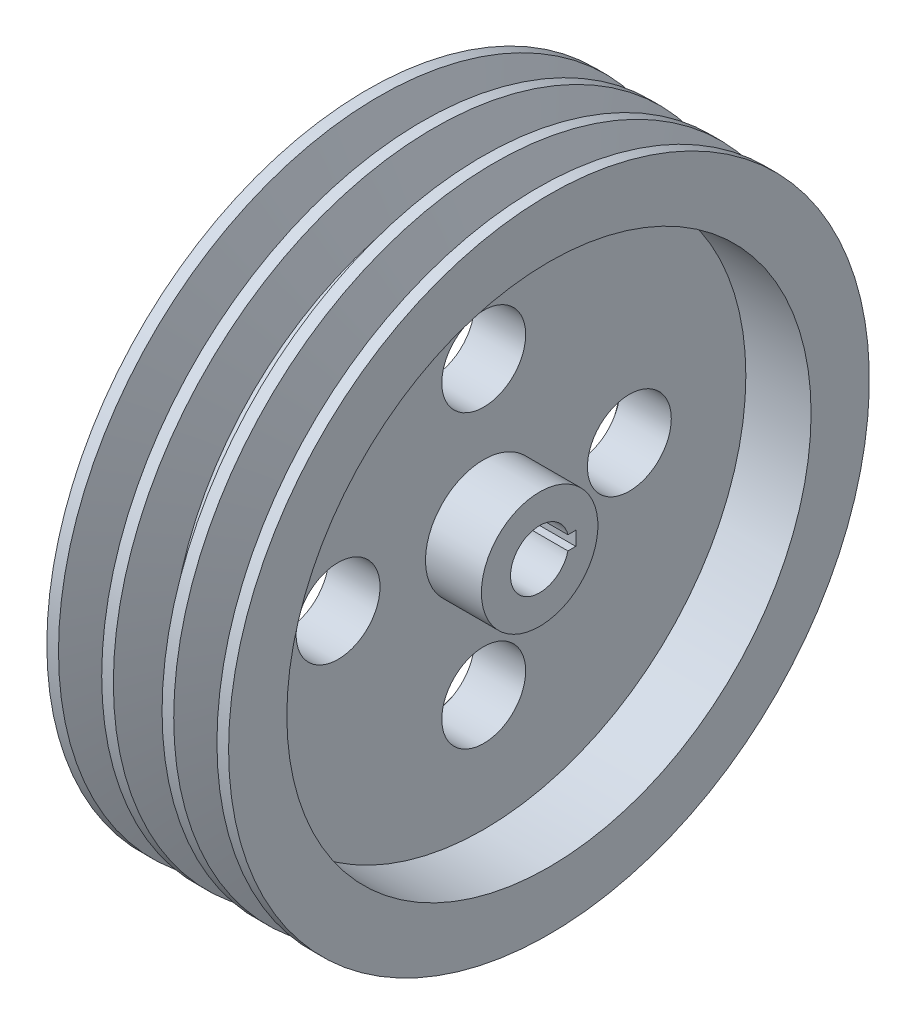
SolidWorks part; units mm, degrees
ref_plane "Front Plane" through (0, 0, 0) normal (0, 0, 1) x (1, 0, 0)
ref_plane "Top Plane" through (0, 0, 0) normal (0, 1, 0) x (1, 0, 0)
ref_plane "Right Plane" through (0, 0, 0) normal (1, 0, 0) x (0, 0, -1)
sketch "Sketch1" plane through (0, 0, 0) normal (0, 0, 1) x (1, 0, 0)
  line L0 (-35, 12.5) -> (-35, 25)
  line L1 (-35, 25) -> (-11, 25)
  line L2 (-11, 25) -> (-11, 112.5)
  line L3 (-11, 112.5) -> (-39, 112.5)
  line L4 (-39, 112.5) -> (-39, 137.5)
  line L5 (-39, 137.5) -> (-34, 137.5)
  line L6 (39, 137.5) -> (39, 112.5)
  line L7 (39, 112.5) -> (11, 112.5)
  line L8 (11, 112.5) -> (11, 25)
  line L9 (11, 25) -> (35, 25)
  line L10 (35, 25) -> (35, 12.5)
  line L11 (35, 12.5) -> (-35, 12.5)
  line L12 (0, 137.5) -> (0, 0) construction
  line L13 (-35, 12.5) -> (-35, 0)
  line L14 (-35, 0) -> (35, 0) construction
  line L15 (35, 0) -> (35, 12.5)
  line L16 (-10.4523, 137.5) -> (-3.9008, 119.5)
  line L17 (39, 137.5) -> (34, 137.5)
  line L18 (34, 137.5) -> (27.4485, 119.5)
  line L19 (27.4485, 119.5) -> (22.0038, 119.5)
  line L20 (22.0038, 119.5) -> (15.4523, 137.5)
  line L21 (24.7262, 119.5) -> (24.7262, 137.5) construction
  line L22 (34, 137.5) -> (39, 137.5)
  line L23 (-39, 137.5) -> (-34, 137.5)
  line L24 (0, 119.5) -> (0, 137.5) construction
  line L25 (-22.0038, 119.5) -> (-15.4523, 137.5)
  line L26 (-27.4485, 119.5) -> (-22.0038, 119.5)
  line L27 (-34, 137.5) -> (-27.4485, 119.5)
  line L28 (39, 137.5) -> (15.4523, 137.5)
  line L29 (-3.9008, 119.5) -> (3.9008, 119.5)
  line L30 (3.9008, 119.5) -> (10.4523, 137.5)
  line L31 (-15.4523, 137.5) -> (-10.4523, 137.5)
  line L32 (10.4523, 137.5) -> (15.4523, 137.5)
  line L33 (-24.7262, 119.5) -> (-24.7262, 145.7446) construction
  point P24 (0, 119.5)
  dimension "D1" = 78
  dimension "D2" = 25
  dimension "D3" = 20
  dimension "D4" = 11
  dimension "D5" = 25
  dimension "D6" = 125
  dimension "D7" = 12.5
  dimension "D8" = 35
  dimension "D9" = 35
  dimension "D10" = 5
  dimension "D11" = 20
  dimension "D12" = 20
  dimension "D13" = 20
  dimension "D14" = 5
  dimension "D15" = 18
  dimension "D16" = 11
  dimension "D17" = 20
  dimension "D18" = 20
revolve "Revolve5" add sketch "Sketch1" angle 360 about L14
sketch "Sketch3" plane through (35, 0, 0) normal (1, 0, 0) x (0, 0, -1)
  line L4 (0, 0) -> (15.5, 0) construction
  line L5 (15.5, 3) -> (15.5, -3)
  line L6 (15.5, 3) -> (12, 3)
  line L7 (15.5, -3) -> (12, -3)
  line L8 (12, -3) -> (12, 3)
  point P2 (15.5, 0)
  dimension "D1" = 6
  dimension "D2" = 3.5
extrude "Cut-Extrude9" cut sketch "Sketch3" against normal through all
sketch "Sketch7" plane through (11, 0, 0) normal (1, 0, 0) x (0, 0, -1)
  circle A0 centre (0, 0) radius 62.5 construction
  circle A1 centre (0, 62.5) radius 18
  circle A2 centre (62.5, 0) radius 18
  circle A3 centre (0, -62.5) radius 18
  circle A4 centre (-62.5, 0) radius 18
  point P5 (0, 0)
  point P6 (0, 0)
  point P14 (0, 0)
  dimension "D1" = 125
  dimension "D2" = 36
  dimension "D3" = 4
extrude "Cut-Extrude10" cut sketch "Sketch7" against normal through all
